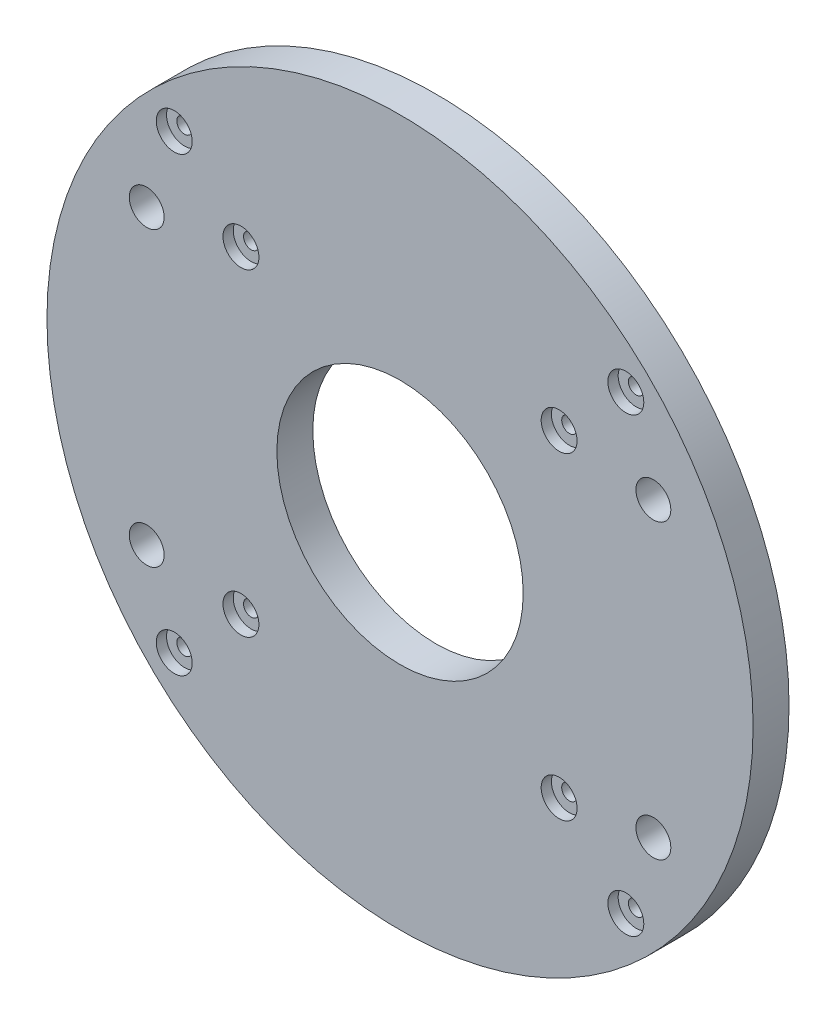
SolidWorks part; units mm, degrees
ref_plane "前视基准面" through (0, 0, 0) normal (0, 0, 1) x (1, 0, 0)
ref_plane "上视基准面" through (0, 0, 0) normal (0, 1, 0) x (1, 0, 0)
ref_plane "右视基准面" through (0, 0, 0) normal (1, 0, 0) x (0, 0, -1)
sketch "草图1" plane through (0, 0, 0) normal (0, 0, 1) x (1, 0, 0)
  arc A0 (7.287, 4.9035) -> (7.287, 8.3035) centre (7.287, 6.6035) ccw
  arc A1 (31.9687, 26.7535) -> (-2.4313, -7.6465) centre (31.9687, -7.6465) ccw
  arc A2 (-2.4313, -7.6465) -> (66.3687, -7.6465) centre (31.9687, -7.6465) ccw
  arc A3 (66.3687, -7.6465) -> (31.9687, 26.7535) centre (31.9687, -7.6465) ccw
  arc A4 (7.287, 8.3035) -> (7.287, 4.9035) centre (7.287, 6.6035) ccw
  arc A5 (56.6504, 8.3035) -> (56.6504, 4.9035) centre (56.6504, 6.6035) ccw
  arc A6 (7.287, -23.5965) -> (7.287, -20.1965) centre (7.287, -21.8965) ccw
  arc A7 (7.287, -20.1965) -> (7.287, -23.5965) centre (7.287, -21.8965) ccw
  arc A8 (56.6504, -20.1965) -> (56.6504, -23.5965) centre (56.6504, -21.8965) ccw
  arc A9 (56.6504, -23.5965) -> (56.6504, -20.1965) centre (56.6504, -21.8965) ccw
  arc A10 (56.6504, 4.9035) -> (56.6504, 8.3035) centre (56.6504, 6.6035) ccw
extrude "凸台-拉伸1" add sketch "草图1" along normal blind 3.5
sketch "草图2" plane through (0, 0, 0) normal (0, 0, -1) x (-1, 0, 0)
  line L0 (-76.9687, -32.6465) -> (13.0313, -32.6465)
  line L1 (-76.9687, -32.6465) -> (-76.9687, 17.3535)
  line L2 (13.0313, -32.6465) -> (13.0313, 17.3535)
  line L3 (-76.9687, 17.3535) -> (13.0313, 17.3535)
  line L4 (-76.9687, -32.6465) -> (13.0313, 17.3535) construction
  line L5 (13.0313, -32.6465) -> (-76.9687, 17.3535) construction
  circle A1 centre (-31.9687, -7.6465) radius 34.4
  circle A2 centre (-31.9687, -7.6465) radius 34.4
  circle M6 centre (-31.9687, -7.6465) radius 34.4
  circle M7 centre (-7.287, 6.6035) radius 1.7
  circle M8 centre (-56.6504, 6.6035) radius 1.7
  circle M9 centre (-7.287, -21.8965) radius 1.7
  circle M10 centre (-56.6504, -21.8965) radius 1.7
  dimension "D2" = 90
  dimension "D3" = 50
  dimension "D1" = 0
extrude "凸台-拉伸2" add sketch "草图2" along normal blind 3 contours L3 L0 M6 M7 M9 M10 M8 | L3 L1 L0 M6 | L3 L0 L2 M6
sketch "草图3" plane through (0, 0, -3) normal (0, 0, -1) x (-1, 0, 0)
  line L0 (-31.9687, 17.3535) -> (-31.9687, -35.8873) construction
  line L1 (13.0313, -7.6465) -> (-76.9687, -7.6465) construction
  line L3 (-47.4687, 7.8535) -> (-16.4687, 7.8535) construction
  line L4 (13.0313, 17.3535) -> (-76.9687, 17.3535)
  line L5 (-76.9687, 17.3535) -> (-76.9687, -32.6465)
  line L6 (-76.9687, -32.6465) -> (13.0313, -32.6465)
  line L7 (13.0313, -32.6465) -> (13.0313, 17.3535)
  line L8 (13.0313, 17.3535) -> (-76.9687, 17.3535)
  line L9 (-76.9687, 17.3535) -> (-76.9687, -32.6465)
  line L10 (-76.9687, -32.6465) -> (13.0313, -32.6465)
  line L11 (13.0313, -32.6465) -> (13.0313, 17.3535)
  line L12 (-47.4687, 7.8535) -> (-47.4687, -23.1465) construction
  line L13 (-47.4687, -23.1465) -> (-16.4687, -23.1465) construction
  line L14 (-16.4687, 7.8535) -> (-16.4687, -23.1465) construction
  line L15 (-47.4687, 7.8535) -> (-16.4687, -23.1465) construction
  line L16 (-47.4687, -23.1465) -> (-16.4687, 7.8535) construction
  line L17 (-53.9687, 14.3535) -> (-9.9687, 14.3535) construction
  line L18 (-53.9687, 14.3535) -> (-53.9687, -29.6465) construction
  line L19 (-53.9687, -29.6465) -> (-9.9687, -29.6465) construction
  line L20 (-9.9687, 14.3535) -> (-9.9687, -29.6465) construction
  line L21 (-53.9687, 14.3535) -> (-9.9687, -29.6465) construction
  line L22 (-53.9687, -29.6465) -> (-9.9687, 14.3535) construction
  circle A0 centre (-47.4687, 7.8535) radius 0.75
  circle A1 centre (-47.4687, -23.1465) radius 0.75
  circle A2 centre (-16.4687, 7.8535) radius 0.75
  circle A3 centre (-16.4687, -23.1465) radius 0.75
  circle A4 centre (-53.9687, 14.3535) radius 0.75
  circle A5 centre (-53.9687, -29.6465) radius 0.75
  circle A6 centre (-9.9687, -29.6465) radius 0.75
  circle A7 centre (-9.9687, 14.3535) radius 0.75
  point P8 (-31.9687, -7.6465)
  point P17 (-31.9687, -7.6465)
  dimension "D4" = 1.5
  dimension "D7" = 1.5
  dimension "D2" = 31
  dimension "D3" = 31
  dimension "D5" = 44
  dimension "D6" = 44
  dimension "D1" = 0
extrude "切除-拉伸1" cut sketch "草图3" against normal through all contours A4 | A0 | A7 | A2 | A3 | A6 | A5 | A1
sketch "草图4" plane through (0, 0, 3.5) normal (0, 0, 1) x (1, 0, 0)
  circle A0 centre (31.9687, -7.6465) radius 12
  circle A1 centre (31.9687, -7.6465) radius 34.4
  circle A2 centre (31.9687, -7.6465) radius 34.4
  dimension "D2" = 24
  dimension "D1" = 0
extrude "切除-拉伸2" cut sketch "草图4" against normal through all contours A0
sketch "草图5" plane through (0, 0, 3.5) normal (0, 0, 1) x (1, 0, 0)
  circle A0 centre (7.287, 6.6035) radius 1.7 construction
  circle A1 centre (31.9687, -7.6465) radius 34.4
  circle A2 centre (31.9687, -7.6465) radius 34.4
  circle A3 centre (9.9687, 14.3535) radius 0.75 construction
  circle A4 centre (16.4687, 7.8535) radius 0.75 construction
  circle A5 centre (7.287, -21.8965) radius 1.7 construction
  circle A6 centre (16.4687, -23.1465) radius 0.75 construction
  circle A7 centre (9.9687, -29.6465) radius 0.75 construction
  circle A8 centre (47.4687, -23.1465) radius 0.75 construction
  circle A9 centre (56.6504, -21.8965) radius 1.7 construction
  circle A10 centre (53.9687, -29.6465) radius 0.75 construction
  circle A11 centre (56.6504, 6.6035) radius 1.7 construction
  circle A12 centre (47.4687, 7.8535) radius 0.75 construction
  circle A13 centre (53.9687, 14.3535) radius 0.75 construction
  circle A14 centre (53.9687, 14.3535) radius 0.75
  circle A15 centre (47.4687, 7.8535) radius 0.75
  circle A16 centre (56.6504, 6.6035) radius 1.7
  circle A17 centre (53.9687, -29.6465) radius 0.75
  circle A18 centre (56.6504, -21.8965) radius 1.7
  circle A19 centre (47.4687, -23.1465) radius 0.75
  circle A20 centre (9.9687, -29.6465) radius 0.75
  circle A21 centre (16.4687, -23.1465) radius 0.75
  circle A22 centre (7.287, -21.8965) radius 1.7
  circle A23 centre (16.4687, 7.8535) radius 0.75
  circle A24 centre (9.9687, 14.3535) radius 0.75
  circle A25 centre (7.287, 6.6035) radius 1.7
  circle A27 centre (16.4687, 7.8535) radius 1.75
  circle A28 centre (9.9687, 14.3535) radius 1.75
  circle A29 centre (53.9687, 14.3535) radius 1.75
  circle A30 centre (47.4687, 7.8535) radius 1.75
  circle A33 centre (47.4687, -23.1465) radius 1.75
  circle A34 centre (53.9687, -29.6465) radius 1.75
  circle A36 centre (16.4687, -23.1465) radius 1.75
  circle A37 centre (9.9687, -29.6465) radius 1.75
  circle M8 centre (16.4687, -23.1465) radius 0.75
  circle M9 centre (9.9687, 14.3535) radius 0.75
  circle M10 centre (47.4687, 7.8535) radius 0.75
  circle M11 centre (9.9687, -29.6465) radius 0.75
  circle M12 centre (47.4687, -23.1465) radius 0.75
  circle M13 centre (53.9687, 14.3535) radius 0.75
  circle M19 centre (53.9687, -29.6465) radius 0.75
  circle M20 centre (16.4687, 7.8535) radius 0.75
  dimension "D2" = 1
  dimension "D1" = 0
extrude "切除-拉伸4" cut sketch "草图5" against normal blind 1 contours A28 M9 | A27 M20 | A30 M10 | A29 M13 | A33 M12 | A36 M8 | A37 M11 | A34 M19
sketch "草图6" plane through (76.9687, 0, 0) normal (1, 0, 0) x (0, 0, -1)
  line L4 (0, 17.3535) -> (0, -32.6465)
  line L5 (0, -32.6465) -> (3, -32.6465)
  line L6 (3, -32.6465) -> (3, 17.3535)
  line L7 (3, 17.3535) -> (0, 17.3535)
  line L8 (0, 17.3535) -> (0, -32.6465)
  line L9 (0, -32.6465) -> (3, -32.6465)
  line L10 (3, -32.6465) -> (3, 17.3535)
  line L11 (3, 17.3535) -> (0, 17.3535)
  dimension "D1" = 0
extrude "切除-拉伸5" cut sketch "草图6" against normal through all
